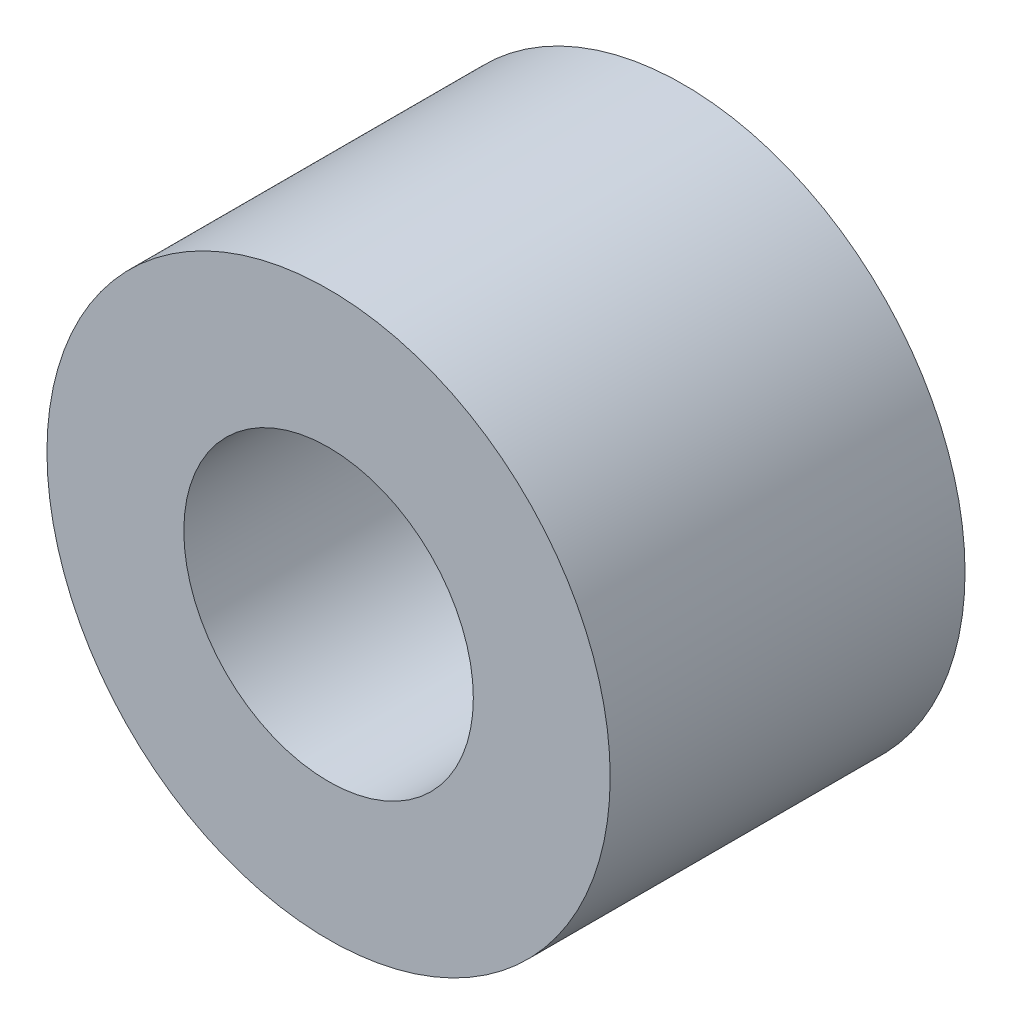
SolidWorks part; units mm, degrees
ref_plane "Front Plane" through (0, 0, 0) normal (0, 0, 1) x (1, 0, 0)
ref_plane "Top Plane" through (0, 0, 0) normal (0, 1, 0) x (1, 0, 0)
ref_plane "Right Plane" through (0, 0, 0) normal (1, 0, 0) x (0, 0, -1)
sketch "Sketch1" plane through (0, 0, 0) normal (0, 0, 1) x (1, 0, 0)
  circle A0 centre (0, 0) radius 3.2639
  circle A1 centre (0, 0) radius 6.35
  dimension "D1" = 12.7
  dimension "D2" = 6.5278
extrude "Boss-Extrude1" add sketch "Sketch1" along normal blind 8.001
equation "\"OD\"= .5"
equation "\"ID\"= .257"
equation "\"L\"= .315"
equation "\"D1@Sketch1\"=\"OD\""
equation "\"D2@Sketch1\"=\"ID\""
equation "\"D1@Boss-Extrude1\"=\"L\""
